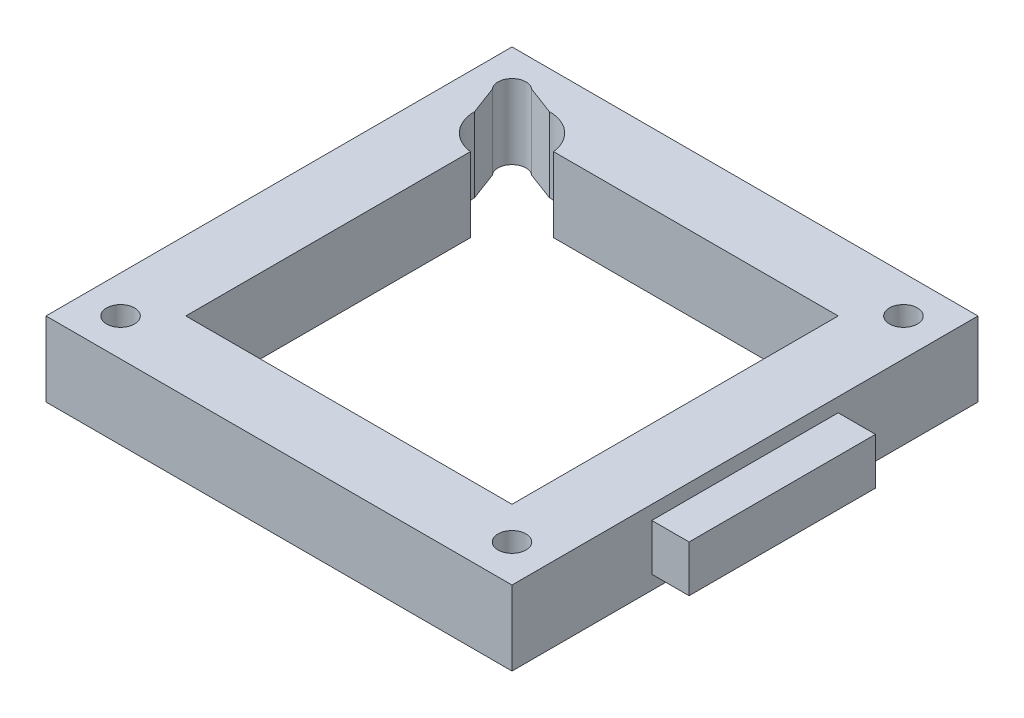
SolidWorks part; units mm, degrees
ref_plane "Front Plane" through (0, 0, 0) normal (0, 0, 1) x (1, 0, 0)
ref_plane "Top Plane" through (0, 0, 0) normal (0, 1, 0) x (1, 0, 0)
ref_plane "Right Plane" through (0, 0, 0) normal (1, 0, 0) x (0, 0, -1)
sketch "Sketch1" plane through (0, 0, 0) normal (0, 1, 0) x (1, 0, 0)
  line L0 (17.5, 17.5) -> (-13.0314, 17.5)
  line L1 (-25, -25) -> (25, -25)
  line L2 (-25, -25) -> (-25, 25)
  line L3 (-25, 25) -> (25, 25)
  line L4 (25, -25) -> (25, 25)
  line L5 (0, 25) -> (0, -25) construction
  line L6 (-25, 0) -> (25, 0) construction
  line L11 (0, 20) -> (0, -20) construction
  line L12 (-20, 0) -> (20, 0) construction
  line L13 (-17.5, -17.5) -> (17.5, -17.5)
  line L16 (17.5, -17.5) -> (17.5, 17.5)
  line L17 (0, 17.5) -> (0, -17.5) construction
  line L18 (-17.5, 0) -> (17.5, 0) construction
  line L19 (-17.5, -17.5) -> (-17.5, 13.0314)
  line L20 (-22.1301, 20.0137) -> (-21, 17)
  line L21 (-20.0137, 22.1301) -> (-17, 21)
  arc A0 (-20.0137, 22.1301) -> (-22.1301, 20.0137) centre (-21, 21) ccw
  circle A1 centre (21, 21) radius 1.5
  circle A2 centre (21, -21) radius 1.5
  circle A3 centre (-21, -21) radius 1.5
  arc A4 (-21, 17) -> (-17, 21) centre (-17, 17) ccw
  point P0 (0, 0)
  point P4 (0, 0)
  point P13 (0, 0)
  dimension "D1" = 50
  dimension "D2" = 50
  dimension "D4" = 35
extrude "Support" add sketch "Sketch1" along normal blind 8 contours L1 L4 L3 L2 A4 L0 L16 L13 L19 L20 A0 L21 A1 A2 A3
sketch "Sketch2" plane through (0, 0, 0) normal (0, 0, 1) x (1, 0, 0)
  line L4 (-10, 1.5) -> (10, 1.5)
  line L5 (-10, 1.5) -> (-10, 6.5)
  line L6 (-10, 6.5) -> (10, 6.5)
  line L7 (10, 1.5) -> (10, 6.5)
  line L8 (0, 6.5) -> (0, 1.5) construction
  line L9 (-10, 4) -> (10, 4) construction
  point P6 (0, 4)
  dimension "D1" = 20
  dimension "D2" = 5
sketch "Sketch3" plane through (0, 0, 0) normal (1, 0, 0) x (0, 0, -1)
  line L4 (-10, 1.5) -> (10, 1.5)
  line L5 (-10, 1.5) -> (-10, 6.5)
  line L6 (-10, 6.5) -> (10, 6.5)
  line L7 (10, 1.5) -> (10, 6.5)
  line L8 (0, 6.5) -> (0, 1.5) construction
  line L9 (-10, 4) -> (10, 4) construction
  point P6 (0, 4)
  dimension "D1" = 20
  dimension "D2" = 5
extrude "North Cut" cut sketch "Sketch2" along normal blind 4 from surface at -25 starting at face at (0, 4, -25)
extrude "East Dowel" add sketch "Sketch3" along normal blind 4 from surface at 25 starting at face at (25, 4, 0)
